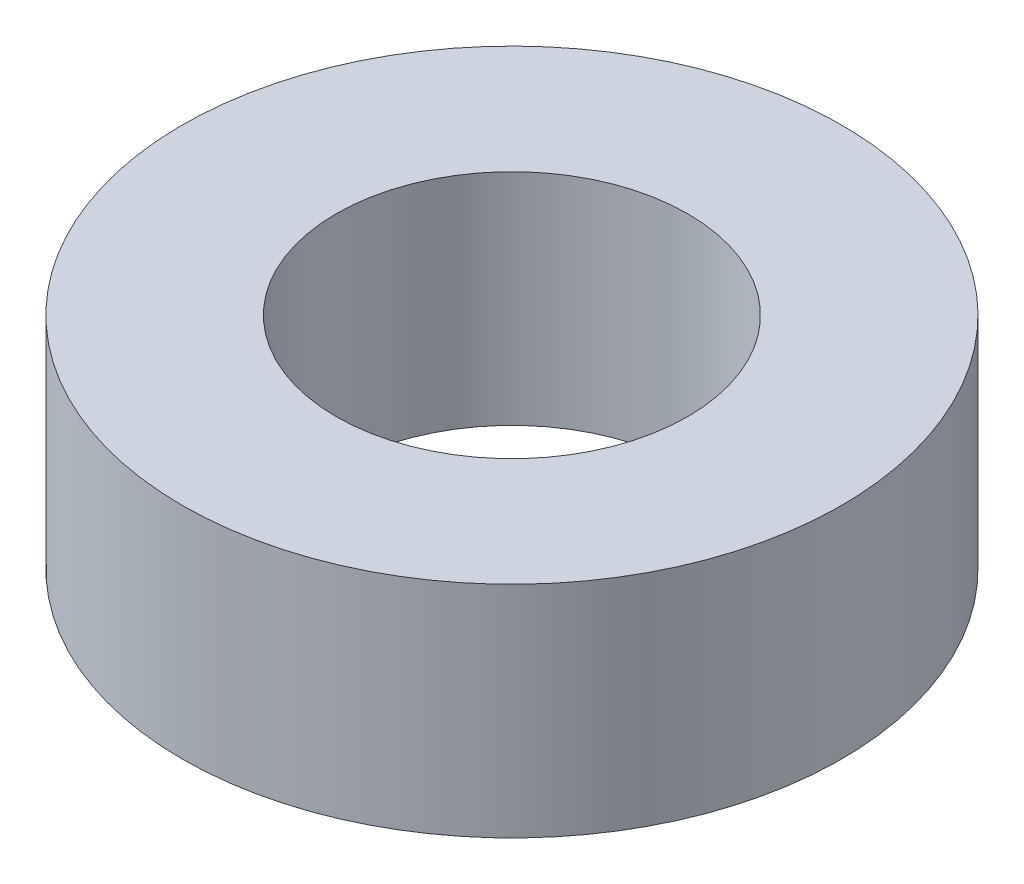
SolidWorks part; units mm, degrees
ref_plane "正面" through (0, 0, 0) normal (0, 0, 1) x (1, 0, 0)
ref_plane "平面" through (0, 0, 0) normal (0, 1, 0) x (1, 0, 0)
ref_plane "右側面" through (0, 0, 0) normal (1, 0, 0) x (0, 0, -1)
sketch "ｽｹｯﾁ1" plane through (0, 0, 0) normal (0, 1, 0) x (1, 0, 0)
  circle A0 centre (0, 0) radius 1.6
  circle A1 centre (0, 0) radius 3
extrude "ﾎﾞｽ - 押し出し1" add sketch "ｽｹｯﾁ1" along normal blind 2
